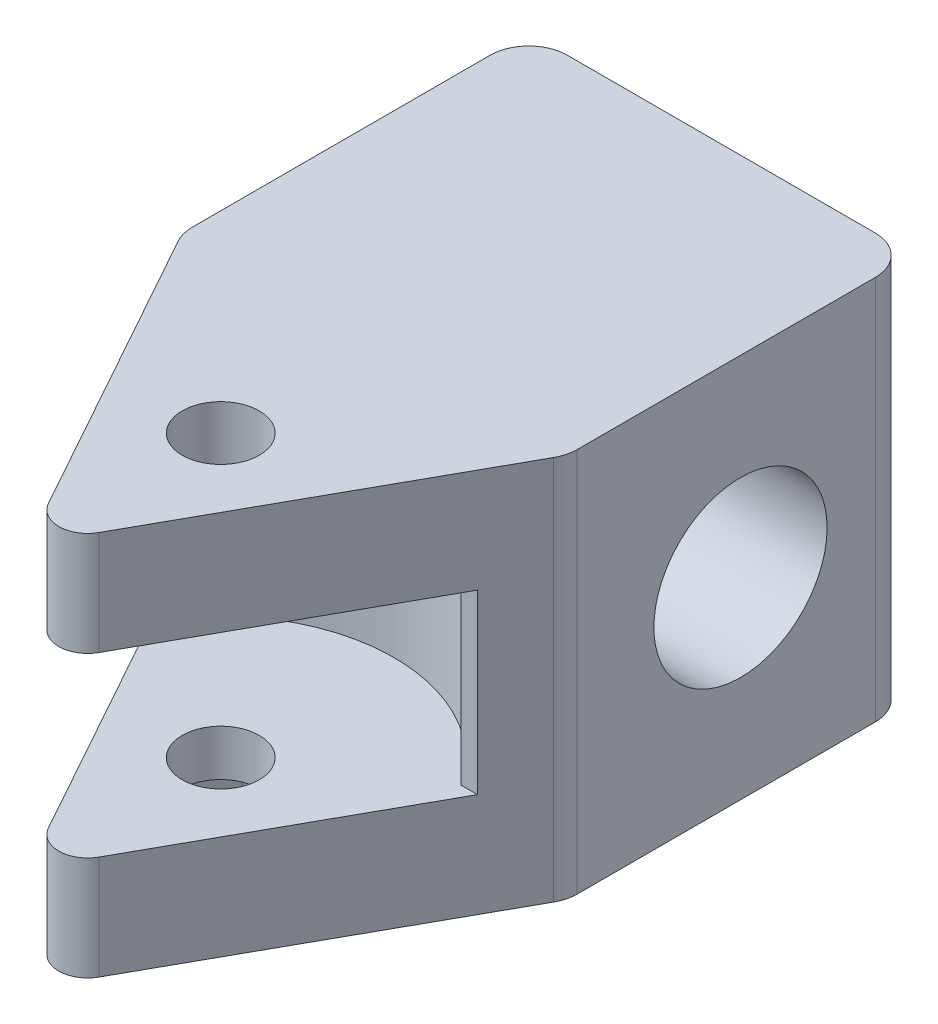
SolidWorks part; units mm, degrees
material "ABS"
ref_plane "前视基准面" through (0, 0, 0) normal (0, 0, 1) x (1, 0, 0)
ref_plane "上视基准面" through (0, 0, 0) normal (0, 1, 0) x (1, 0, 0)
ref_plane "右视基准面" through (0, 0, 0) normal (1, 0, 0) x (0, 0, -1)
sketch "Sketch2" plane through (0, 0, 0) normal (0, 1, 0) x (1, 0, 0)
  line L0 (-10, -9) -> (0, -27)
  line L1 (-10, 9) -> (10, 9)
  line L2 (-10, 9) -> (-10, -9)
  line L3 (-10, -9) -> (10, -9)
  line L4 (10, 9) -> (10, -9)
  line L5 (0, -9) -> (0, 9) construction
  line L6 (-10, 0) -> (10, 0) construction
  line L7 (0, -27) -> (10, -9)
  circle A0 centre (0, -17) radius 2
  point P0 (0, 0)
  dimension "D4" = 4
  dimension "D1" = 18
  dimension "D2" = 20
  dimension "D3" = 18
  dimension "D5" = 8
extrude "Boss-Extrude1" add sketch "Sketch2" along normal mid plane 20 contours L4 L1 L2 L3 | L0 L7 L3
sketch "Sketch4" plane through (0, 0, 0) normal (1, 0, 0) x (0, 0, -1)
  line L0 (0, 0) -> (-23.8384, 0) construction
  line L1 (-27, 10) -> (-27, -10) construction
  line L2 (-12, -4.6) -> (-27, -4.6)
  line L3 (-12, -4.6) -> (-12, 4.6)
  line L4 (-12, 4.6) -> (-27, 4.6)
  line L5 (-27, -4.6) -> (-27, 4.6)
  line L6 (-19.5, 4.6) -> (-19.5, -4.6) construction
  line L7 (-12, 0) -> (-27, 0) construction
  line L8 (-9, 0) -> (9, 0) construction
  point P3 (-19.5, 0)
  dimension "D1" = 9.2
  dimension "D2" = 15
extrude "Cut-Extrude2" cut sketch "Sketch4" against normal through all both and the other way through all
sketch "Sketch3" plane through (10, 0, 0) normal (1, 0, 0) x (0, 0, -1)
  circle A0 centre (0, 0) radius 4.5
  dimension "D1" = 9
extrude "Cut-Extrude1" cut sketch "Sketch3" against normal up to next
fillet "Fillet3" radius 1.5 2 edges at (0, 7.3, 27) (0, -7.3, 27)
fillet "Fillet4" radius 2 4 edges at (10, 0, -9) (-10, 0, -9) (-10, 0, 9) (10, 0, 9)
sketch "Sketch5" plane through (0, 0, 0) normal (0, 1, 0) x (1, 0, 0)
  circle A0 centre (0, -17) radius 9
  dimension "D1" = 18
extrude "Cut-Extrude3" cut sketch "Sketch5" against normal up to surface and the other way up to surface up to face at (0, -4.6, 15) other way up to face at (0, 4.6, 19)
sketch "Sketch8" plane through (0, -10, 0) normal (0, -1, 0) x (1, 0, 0)
  line L138 (2.2055, 13.66) -> (3.1004, 15.21)
  line L139 (0, 13.42) -> (1.7898, 13.42)
  line L140 (-1.7898, 13.42) -> (0, 13.42)
  line L141 (-3.1004, 15.21) -> (-2.2055, 13.66)
  line L142 (-3.9953, 16.76) -> (-3.1004, 15.21)
  line L143 (-3.1004, 18.79) -> (-3.9953, 17.24)
  line L144 (-2.2055, 20.34) -> (-3.1004, 18.79)
  line L145 (0, 20.58) -> (-1.7898, 20.58)
  line L146 (1.7898, 20.58) -> (0, 20.58)
  line L147 (3.1004, 18.79) -> (2.2055, 20.34)
  line L148 (3.9953, 17.24) -> (3.1004, 18.79)
  line L149 (3.1004, 15.21) -> (3.9953, 16.76)
  arc A69 (1.7898, 13.42) -> (2.2055, 13.66) centre (1.7898, 13.9) ccw
  arc A70 (-2.2055, 13.66) -> (-1.7898, 13.42) centre (-1.7898, 13.9) ccw
  arc A71 (-3.9953, 17.24) -> (-3.9953, 16.76) centre (-3.5796, 17) ccw
  arc A72 (-1.7898, 20.58) -> (-2.2055, 20.34) centre (-1.7898, 20.1) ccw
  arc A73 (2.2055, 20.34) -> (1.7898, 20.58) centre (1.7898, 20.1) ccw
  arc A74 (3.9953, 16.76) -> (3.9953, 17.24) centre (3.5796, 17) ccw
extrude "Cut-Extrude4" cut sketch "Sketch8" against normal blind 3
